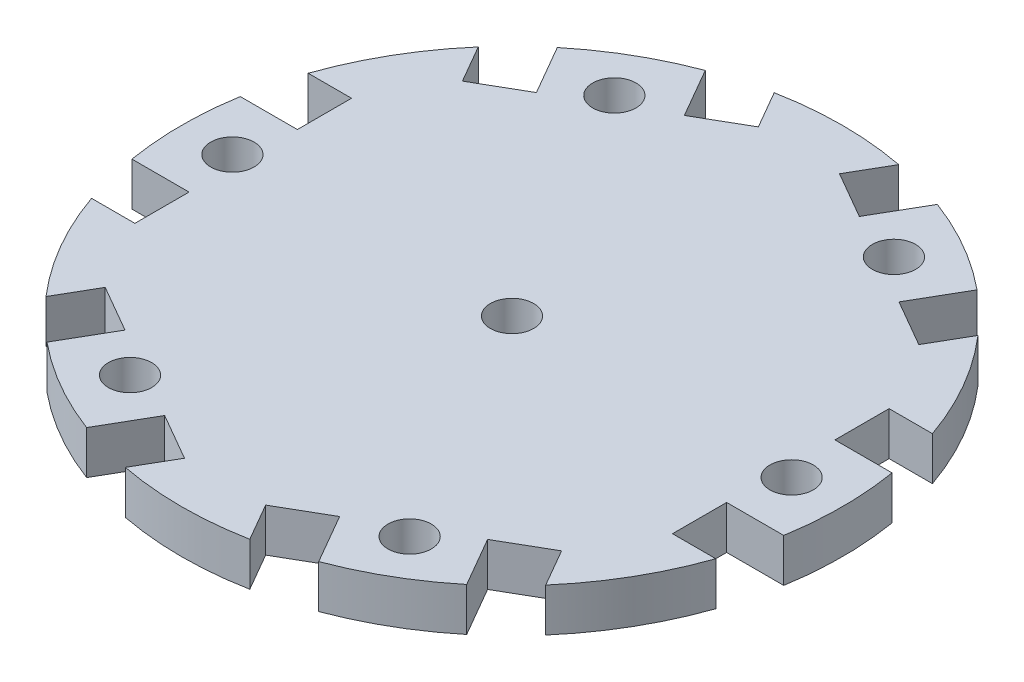
SolidWorks part; units mm, degrees
ref_plane "Alzado" through (0, 0, 0) normal (0, 0, 1) x (1, 0, 0)
ref_plane "Planta" through (0, 0, 0) normal (0, 1, 0) x (1, 0, 0)
ref_plane "Vista lateral" through (0, 0, 0) normal (1, 0, 0) x (0, 0, -1)
sketch "Croquis1" plane through (0, 0, 0) normal (0, 1, 0) x (1, 0, 0)
  circle A0 centre (0, 0) radius 30.5
extrude "Saliente-Extruir1" add sketch "Croquis1" along normal blind 4
sketch "Croquis2" plane through (0, 4, 0) normal (0, 1, 0) x (1, 0, 0)
  circle A0 centre (0, 0) radius 2
extrude "Cortar-Extruir1" cut sketch "Croquis2" against normal blind 4
sketch "Croquis5" plane through (0, 4, 0) normal (0, 1, 0) x (1, 0, 0)
  line L1 (28.8141, -5) -> (30.0874, -5)
  line L2 (28.8141, 5) -> (30.0874, 5)
  line L3 (-24.8141, 10) -> (-28.8141, 10)
  line L4 (24.8141, -5) -> (24.8141, -10)
  line L5 (-24.8141, -10) -> (-28.8141, -10)
  line L6 (24.8141, -5) -> (28.8141, -5)
  line L7 (24.8141, 5) -> (24.8141, 10)
  line L8 (-24.8141, 5) -> (-28.8141, 5)
  line L9 (-24.8141, 5) -> (-24.8141, 10)
  line L10 (-24.8141, -5) -> (-28.8141, -5)
  line L11 (-24.8141, -5) -> (-24.8141, -10)
  line L12 (24.8141, 5) -> (28.8141, 5)
  line L13 (24.8141, -10) -> (28.8141, -10)
  line L14 (24.8141, 10) -> (28.8141, 10)
  line L15 (-28.8141, 5) -> (-30.0874, 5)
  line L16 (-28.8141, -5) -> (-30.0874, -5)
  line L17 (18.7372, 22.4537) -> (19.3738, 23.5564)
  line L18 (-24.8141, 0) -> (-12.407, -21.4896)
  line L19 (-12.407, -21.4896) -> (12.407, -21.4896)
  line L20 (12.407, -21.4896) -> (24.8141, 0)
  line L21 (24.8141, 0) -> (12.407, 21.4896)
  line L22 (12.407, 21.4896) -> (-12.407, 21.4896)
  line L23 (-12.407, 21.4896) -> (-24.8141, 0)
  line L24 (-21.0673, -16.4896) -> (-23.0673, -19.9537)
  line L25 (-3.7468, -26.4896) -> (-5.7468, -29.9537)
  line L26 (-16.7372, -18.9896) -> (-18.7372, -22.4537)
  line L27 (-16.7372, -18.9896) -> (-21.0673, -16.4896)
  line L28 (-8.0769, -23.9896) -> (-10.0769, -27.4537)
  line L29 (-8.0769, -23.9896) -> (-3.7468, -26.4896)
  line L30 (-18.7372, -22.4537) -> (-19.3738, -23.5564)
  line L31 (-10.0769, -27.4537) -> (-10.7136, -28.5564)
  line L32 (10.0769, 27.4537) -> (10.7136, 28.5564)
  line L33 (16.7372, 18.9896) -> (21.0673, 16.4896)
  line L34 (16.7372, 18.9896) -> (18.7372, 22.4537)
  line L35 (8.0769, 23.9896) -> (3.7468, 26.4896)
  line L36 (8.0769, 23.9896) -> (10.0769, 27.4537)
  line L37 (21.0673, 16.4896) -> (23.0673, 19.9537)
  line L38 (3.7468, 26.4896) -> (5.7468, 29.9537)
  line L39 (-3.7468, 26.4896) -> (-5.7468, 29.9537)
  line L40 (-21.0673, 16.4896) -> (-23.0673, 19.9537)
  line L41 (-8.0769, 23.9896) -> (-10.0769, 27.4537)
  line L42 (-8.0769, 23.9896) -> (-3.7468, 26.4896)
  line L43 (-16.7372, 18.9896) -> (-18.7372, 22.4537)
  line L44 (-16.7372, 18.9896) -> (-21.0673, 16.4896)
  line L45 (-10.0769, 27.4537) -> (-10.7136, 28.5564)
  line L46 (-18.7372, 22.4537) -> (-19.3738, 23.5564)
  line L47 (10.0769, -27.4537) -> (10.7136, -28.5564)
  line L48 (18.7372, -22.4537) -> (19.3738, -23.5564)
  line L49 (8.0769, -23.9896) -> (3.7468, -26.4896)
  line L50 (8.0769, -23.9896) -> (10.0769, -27.4537)
  line L51 (16.7372, -18.9896) -> (21.0673, -16.4896)
  line L52 (16.7372, -18.9896) -> (18.7372, -22.4537)
  line L53 (3.7468, -26.4896) -> (5.7468, -29.9537)
  line L54 (21.0673, -16.4896) -> (23.0673, -19.9537)
  circle A0 centre (0, 0) radius 21.4896 construction
  circle A1 centre (0, 0) radius 30.5 construction
  arc A2 (-28.8141, 10) -> (-30.0874, 5) centre (0, 0) ccw
  arc A3 (-5.7468, 29.9537) -> (-10.7136, 28.5564) centre (0, 0) ccw
  arc A4 (-30.0874, -5) -> (-28.8141, -10) centre (0, 0) ccw
  arc A5 (30.0874, -5) -> (28.8141, -10) centre (0, 0) cw
  arc A6 (28.8141, 10) -> (30.0874, 5) centre (0, 0) cw
  arc A7 (-23.0673, -19.9537) -> (-19.3738, -23.5564) centre (0, 0) ccw
  arc A8 (-10.7136, -28.5564) -> (-5.7468, -29.9537) centre (0, 0) ccw
  arc A9 (-19.3738, 23.5564) -> (-23.0673, 19.9537) centre (0, 0) ccw
  arc A10 (19.3738, 23.5564) -> (23.0673, 19.9537) centre (0, 0) cw
  arc A11 (5.7468, 29.9537) -> (10.7136, 28.5564) centre (0, 0) cw
  arc A12 (10.7136, -28.5564) -> (5.7468, -29.9537) centre (0, 0) cw
  arc A13 (23.0673, -19.9537) -> (19.3738, -23.5564) centre (0, 0) cw
  circle M2 centre (0, 0) radius 30.5
extrude "Cortar-Extruir3" cut sketch "Croquis5" against normal blind 4 contours L15 L8 L9 L3 M2 | L14 L7 L12 L2 M2 | L4 L13 L1 L6 M2 | L54 L51 L52 L48 M2 | L49 L53 L47 L50 M2 | L28 L31 L25 L29 M2 | L30 L26 L27 L24 M2 | L10 L16 L5 L11 M2 | L43 L46 L40 L44 M2 | L45 L41 L42 L39 M2 | L38 L35 L36 L32 M2 | L33 L37 L17 L34 M2
sketch "Croquis7" plane through (0, 4, 0) normal (0, 1, 0) x (1, 0, 0)
  line L2 (25.8141, 0) -> (12.907, 22.3556)
  line L3 (12.907, 22.3556) -> (-12.907, 22.3556)
  line L4 (-12.907, 22.3556) -> (-25.8141, 0)
  line L5 (-25.8141, 0) -> (-12.907, -22.3556)
  line L6 (-12.907, -22.3556) -> (12.907, -22.3556)
  line L7 (12.907, -22.3556) -> (25.8141, 0)
  circle A0 centre (25.8141, 0) radius 2
  circle A4 centre (-25.8141, 0) radius 2
  circle A5 centre (0, 0) radius 22.3556 construction
  circle A6 centre (12.907, 22.3556) radius 2
  circle A7 centre (-12.907, -22.3556) radius 2
  circle A8 centre (-12.907, 22.3556) radius 2
  circle A9 centre (12.907, -22.3556) radius 2
extrude "Cortar-Extruir4" cut sketch "Croquis7" against normal blind 10 contours A8 L4 L3 | A4 L4 L5 | A4 L5 L4 | A8 L3 L4 | L2 A6 L3 | L3 A6 L2 | L7 A0 L2 | L2 A0 L7 | A7 L5 L6 | A7 L6 L5 | L6 A9 L7 | L7 A9 L6
